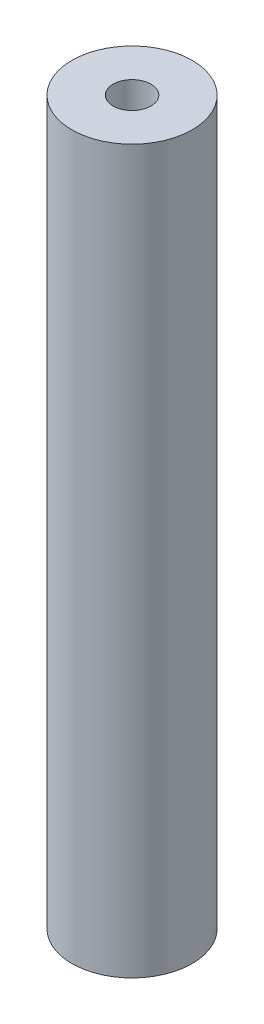
SolidWorks part; units mm, degrees
ref_plane "Front Plane" through (0, 0, 0) normal (0, 0, 1) x (1, 0, 0)
ref_plane "Top Plane" through (0, 0, 0) normal (0, 1, 0) x (1, 0, 0)
ref_plane "Right Plane" through (0, 0, 0) normal (1, 0, 0) x (0, 0, -1)
sketch "Sketch1" plane through (0, 0, 0) normal (0, 1, 0) x (1, 0, 0)
  circle A0 centre (0, 0) radius 6.35
  dimension "D1" = 12.7
extrude "Boss-Extrude1" add sketch "Sketch1" along normal blind 76.2
sketch "Sketch2" plane through (0, 0, 0) normal (0, -1, 0) x (1, 0, 0)
  circle A0 centre (0, 0) radius 2
  dimension "D1" = 4
extrude "Cut-Extrude1" cut sketch "Sketch2" against normal blind 7
sketch "Sketch3" plane through (0, 76.2, 0) normal (0, 1, 0) x (1, 0, 0)
  circle A0 centre (0, 0) radius 2
  dimension "D1" = 4
extrude "Cut-Extrude2" cut sketch "Sketch3" against normal blind 7
